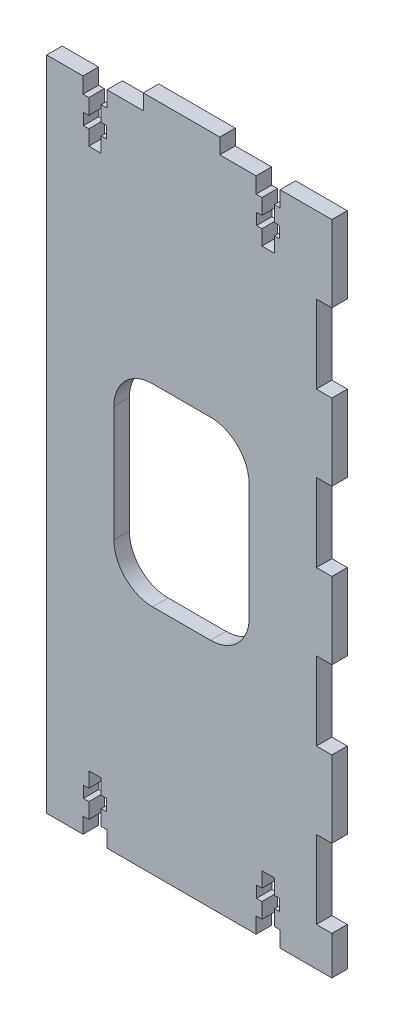
SolidWorks part; units mm, degrees
ref_plane "Front Plane" through (0, 0, 0) normal (0, 0, 1) x (1, 0, 0)
ref_plane "Top Plane" through (0, 0, 0) normal (0, 1, 0) x (1, 0, 0)
ref_plane "Right Plane" through (0, 0, 0) normal (1, 0, 0) x (0, 0, -1)
sketch "Sketch1" plane through (0, 0, 0) normal (0, 0, 1) x (1, 0, 0)
  line L0 (-9.9, 85) -> (-9.9, 89)
  line L1 (-34.9, 85) -> (-9.9, 85)
  line L2 (-34.9, 85) -> (-34.9, -85)
  line L3 (-34.9, -85) -> (34.9, -85)
  line L4 (34.9, 85) -> (34.9, -85)
  line L5 (-34.9, 85) -> (34.9, -85) construction
  line L6 (-34.9, -85) -> (34.9, 85) construction
  line L7 (-9.9, 89) -> (9.9, 89)
  line L8 (9.9, 89) -> (9.9, 85)
  line L9 (9.9, 85) -> (34.9, 85)
  point P0 (0, 0)
  point P8 (0, 89)
  dimension "D1" = 170
  dimension "D2" = 69.8
  dimension "D3" = 19.8
  dimension "D4" = 4
extrude "Boss-Extrude1" add sketch "Sketch1" along normal blind 4
sketch "Sketch3" plane through (0, 0, 0) normal (0, 0, -1) x (-1, 0, 0)
  line L0 (22.4, 85) -> (22.4, 70) construction
  line L1 (9.9, 85) -> (34.9, 85) construction
  line L2 (25.5, 85) -> (25.5, 80.9)
  line L3 (25.5, 80.9) -> (24, 80.9)
  line L4 (24, 80.9) -> (24, 76.9)
  line L5 (24, 76.9) -> (25.4, 76.9)
  line L6 (25.4, 76.9) -> (25.4, 73.9)
  line L7 (25.4, 73.9) -> (24, 73.9)
  line L8 (24, 73.9) -> (24, 70)
  line L9 (24, 70) -> (20.8, 70)
  line L10 (20.8, 73.9) -> (20.8, 70)
  line L11 (19.4, 73.9) -> (20.8, 73.9)
  line L12 (19.4, 76.9) -> (19.4, 73.9)
  line L13 (20.8, 76.9) -> (19.4, 76.9)
  line L14 (20.8, 80.9) -> (20.8, 76.9)
  line L15 (19.3, 80.9) -> (20.8, 80.9)
  line L16 (19.3, 85) -> (19.3, 80.9)
  line L17 (0, 89) -> (0, -85) construction
  line L18 (-9.9, 89) -> (9.9, 89) construction
  line L19 (34.9, -85) -> (-34.9, -85) construction
  line L20 (-34.9, 0) -> (34.9, 0) construction
  line L21 (-34.9, -85) -> (-34.9, 85) construction
  line L22 (34.9, 85) -> (34.9, -85) construction
  line L23 (-22.4, 85) -> (-22.4, 70) construction
  line L24 (-19.3, 85) -> (-19.3, 80.9)
  line L25 (-19.3, 80.9) -> (-20.8, 80.9)
  line L26 (-20.8, 80.9) -> (-20.8, 76.9)
  line L27 (-20.8, 76.9) -> (-19.4, 76.9)
  line L28 (-19.4, 76.9) -> (-19.4, 73.9)
  line L29 (-19.4, 73.9) -> (-20.8, 73.9)
  line L30 (-20.8, 73.9) -> (-20.8, 70)
  line L31 (-24, 70) -> (-20.8, 70)
  line L32 (-24, 73.9) -> (-24, 70)
  line L33 (-25.4, 73.9) -> (-24, 73.9)
  line L34 (-25.4, 76.9) -> (-25.4, 73.9)
  line L35 (-24, 76.9) -> (-25.4, 76.9)
  line L36 (-24, 80.9) -> (-24, 76.9)
  line L37 (-25.5, 80.9) -> (-24, 80.9)
  line L38 (-25.5, 85) -> (-25.5, 80.9)
  line L39 (-22.4, -85) -> (-22.4, -70) construction
  line L40 (22.4, -85) -> (22.4, -70) construction
  line L41 (-25.5, -85) -> (-25.5, -80.9)
  line L42 (-25.5, -80.9) -> (-24, -80.9)
  line L43 (-24, -80.9) -> (-24, -76.9)
  line L44 (-24, -76.9) -> (-25.4, -76.9)
  line L45 (-25.4, -76.9) -> (-25.4, -73.9)
  line L46 (-25.4, -73.9) -> (-24, -73.9)
  line L47 (-24, -73.9) -> (-24, -70)
  line L48 (-24, -70) -> (-20.8, -70)
  line L49 (-20.8, -73.9) -> (-20.8, -70)
  line L50 (-19.4, -73.9) -> (-20.8, -73.9)
  line L51 (-19.4, -76.9) -> (-19.4, -73.9)
  line L52 (-20.8, -76.9) -> (-19.4, -76.9)
  line L53 (-20.8, -80.9) -> (-20.8, -76.9)
  line L54 (-19.3, -80.9) -> (-20.8, -80.9)
  line L55 (-19.3, -85) -> (-19.3, -80.9)
  line L56 (19.3, -85) -> (19.3, -80.9)
  line L57 (19.3, -80.9) -> (20.8, -80.9)
  line L58 (20.8, -80.9) -> (20.8, -76.9)
  line L59 (20.8, -76.9) -> (19.4, -76.9)
  line L60 (19.4, -76.9) -> (19.4, -73.9)
  line L61 (19.4, -73.9) -> (20.8, -73.9)
  line L62 (20.8, -73.9) -> (20.8, -70)
  line L63 (24, -70) -> (20.8, -70)
  line L64 (24, -73.9) -> (24, -70)
  line L65 (25.4, -73.9) -> (24, -73.9)
  line L66 (25.4, -76.9) -> (25.4, -73.9)
  line L67 (24, -76.9) -> (25.4, -76.9)
  line L68 (24, -80.9) -> (24, -76.9)
  line L69 (25.5, -80.9) -> (24, -80.9)
  line L70 (25.5, -85) -> (25.5, -80.9)
  line L71 (19.3, 85) -> (25.5, 85)
  line L72 (-25.5, 85) -> (-19.3, 85)
  line L73 (19.3, -85) -> (25.5, -85)
  line L74 (-25.5, -85) -> (-19.3, -85)
  point P6 (24, 78.9)
  dimension "D1" = 15
  dimension "D2" = 4.1
  dimension "D3" = 4
  dimension "D4" = 3
  dimension "D5" = 6.2
  dimension "D6" = 3.2
  dimension "D7" = 6
extrude "Cut-Extrude1" cut sketch "Sketch3" against normal through all
sketch "Sketch4" plane through (0, 0, 0) normal (0, 0, -1) x (-1, 0, 0)
  line L0 (-38.9, 45) -> (-38.9, 25.2)
  line L1 (-34.9, 85) -> (-38.9, 85)
  line L2 (-34.9, 85) -> (-34.9, 65.2)
  line L3 (-34.9, 65.2) -> (-38.9, 65.2)
  line L4 (-38.9, 85) -> (-38.9, 65.2)
  line L5 (-34.9, 45) -> (-38.9, 45)
  line L6 (-34.9, 25.2) -> (-38.9, 25.2)
  line L7 (-38.9, 5) -> (-38.9, -14.8)
  line L8 (-34.9, 5) -> (-38.9, 5)
  line L9 (-34.9, -14.8) -> (-38.9, -14.8)
  line L10 (-38.9, -35) -> (-38.9, -54.8)
  line L11 (-34.9, -35) -> (-38.9, -35)
  line L12 (-34.9, -54.8) -> (-38.9, -54.8)
  line L13 (-34.9, 45) -> (-34.9, 25.2)
  line L14 (-34.9, 5) -> (-34.9, -14.8)
  line L15 (-34.9, -35) -> (-34.9, -54.8)
  dimension "D1" = 4
  dimension "D2" = 19.8
  dimension "D3" = 4
extrude "Boss-Extrude2" add sketch "Sketch4" against normal up to surface (4 mm away) up to face at (0, 4.8333, 4)
sketch "Sketch5" plane through (0, 0, 0) normal (0, 0, -1) x (-1, 0, 0)
  line L0 (-39, -74.8) -> (-35, -74.8) construction
  line L1 (-34.9, -85) -> (-38.9, -85)
  line L2 (-34.9, -85) -> (-34.9, -75)
  line L3 (-34.9, -75) -> (-38.9, -75)
  line L4 (-38.9, -85) -> (-38.9, -75)
  dimension "D1" = 4
  dimension "D2" = 0.2
extrude "Boss-Extrude3" add sketch "Sketch5" against normal blind 4
sketch "Sketch6" plane through (0, 0, 0) normal (0, 0, -1) x (-1, 0, 0)
  line L1 (-7.5, 25) -> (7.5, 25)
  line L2 (-17.5, 15) -> (-17.5, -15)
  line L3 (-7.5, -25) -> (7.5, -25)
  line L4 (17.5, 15) -> (17.5, -15)
  line L5 (-17.5, 25) -> (17.5, -25) construction
  line L6 (-17.5, -25) -> (17.5, 25) construction
  arc A0 (-17.5, -15) -> (-7.5, -25) centre (-7.5, -15) ccw
  arc A1 (7.5, -25) -> (17.5, -15) centre (7.5, -15) ccw
  arc A2 (7.5, 25) -> (17.5, 15) centre (7.5, 15) cw
  arc A3 (-7.5, 25) -> (-17.5, 15) centre (-7.5, 15) ccw
  point P0 (0, 0)
  dimension "D3" = 10
  dimension "D1" = 50
  dimension "D2" = 35
extrude "Cut-Extrude2" cut sketch "Sketch6" against normal through all
